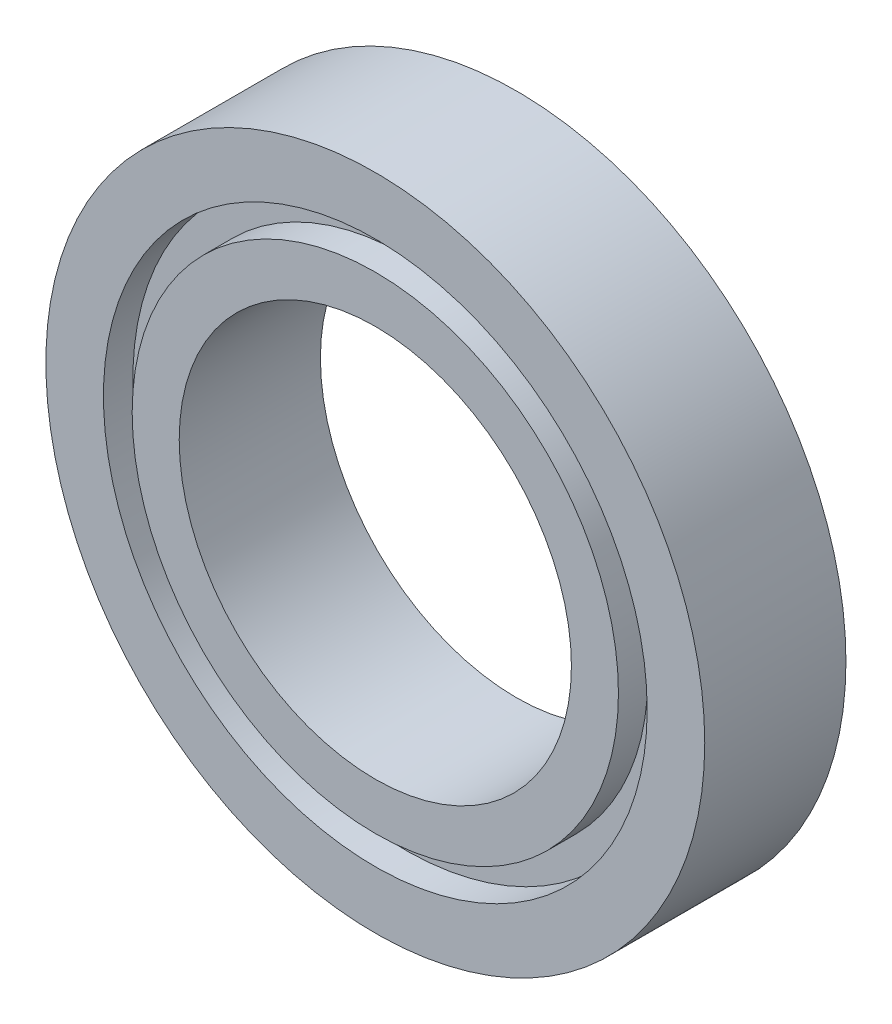
SolidWorks part; units mm, degrees
material "普通碳钢"
ref_plane "前视基准面" through (0, 0, 0) normal (0, 0, 1) x (1, 0, 0)
ref_plane "上视基准面" through (0, 0, 0) normal (0, 1, 0) x (1, 0, 0)
ref_plane "右视基准面" through (0, 0, 0) normal (1, 0, 0) x (0, 0, -1)
sketch "草图1" plane through (0, 0, 0) normal (0, 0, 1) x (1, 0, 0)
  circle A0 centre (0, 0) radius 21
  circle A1 centre (0, 0) radius 12.5
  dimension "D1" = 42
  dimension "D2" = 25
extrude "凸台-拉伸1" add sketch "草图1" along normal mid plane 9
sketch "草图5" plane through (0, 0, 0) normal (1, 0, 0) x (0, 0, -1)
  line L0 (0, 0) -> (19.1867, 0) construction
  line L1 (-4.5, 21) -> (-4.5, -21) construction
  line L2 (-4.5, 15.4981) -> (-2.6244, 15.4981)
  line L3 (-4.5, 15.4981) -> (-4.5, 17.3301)
  line L4 (-4.5, 17.3301) -> (-2.6244, 17.3301)
  line L5 (-2.6244, 15.4981) -> (-2.6244, 17.3301)
  line L6 (0, 22.6369) -> (0, 7.0241) construction
  line L7 (2.6244, 15.4981) -> (2.6244, 17.3301)
  line L8 (4.5, 17.3301) -> (2.6244, 17.3301)
  line L9 (4.5, 15.4981) -> (4.5, 17.3301)
  line L10 (4.5, 15.4981) -> (2.6244, 15.4981)
revolve "切除-旋转1" cut sketch "草图5" angle 360 about L0
